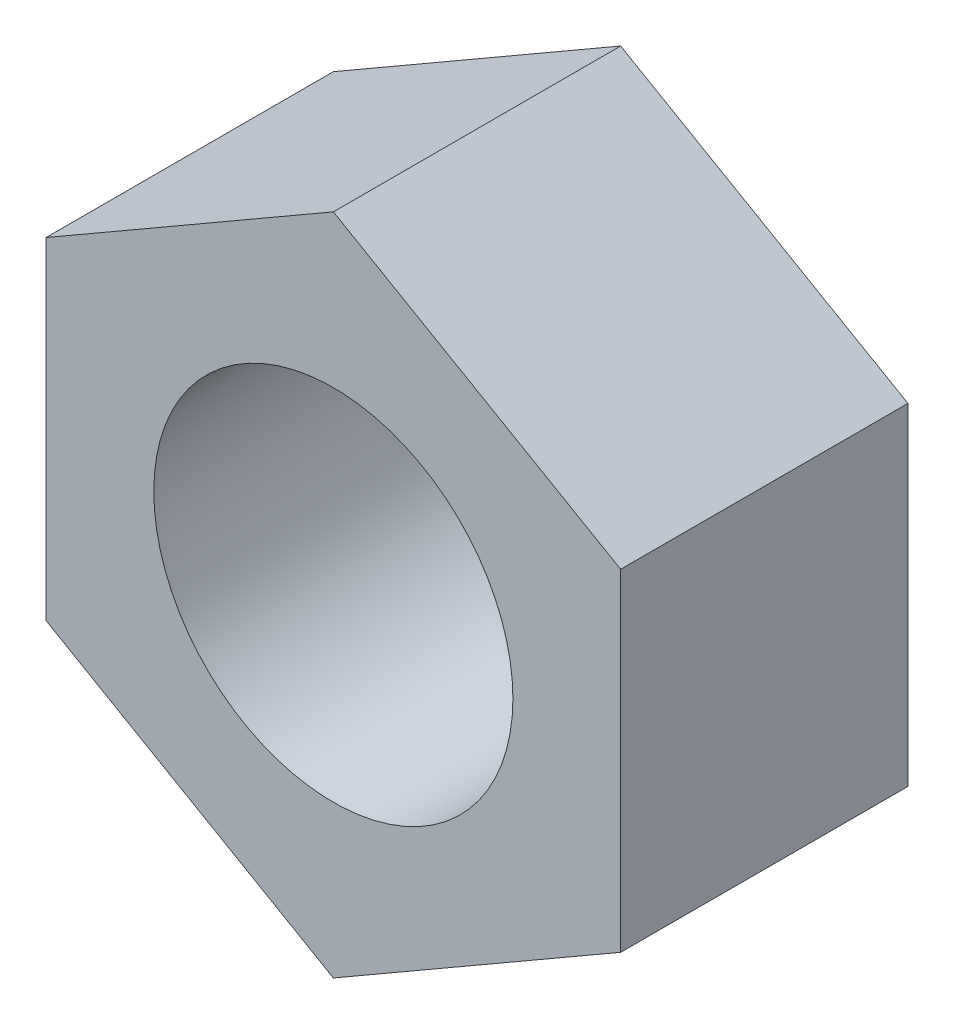
SolidWorks part; units mm, degrees
ref_plane "Přední rovina" through (0, 0, 0) normal (0, 0, 1) x (1, 0, 0)
ref_plane "Horní rovina" through (0, 0, 0) normal (0, 1, 0) x (1, 0, 0)
ref_plane "Pravá rovina" through (0, 0, 0) normal (1, 0, 0) x (0, 0, -1)
sketch "Skica1" plane through (0, 0, 0) normal (0, 0, 1) x (1, 0, 0)
  line L1 (0, -2.7713) -> (2.4, -1.3856)
  line L2 (2.4, -1.3856) -> (2.4, 1.3856)
  line L3 (2.4, 1.3856) -> (0, 2.7713)
  line L4 (0, 2.7713) -> (-2.4, 1.3856)
  line L5 (-2.4, 1.3856) -> (-2.4, -1.3856)
  line L6 (-2.4, -1.3856) -> (0, -2.7713)
  circle A0 centre (0, 0) radius 1.5
  circle A1 centre (0, 0) radius 2.4 construction
  dimension "D1" = 3
  dimension "D2" = 4.8
extrude "Přidat vysunutím1" add sketch "Skica1" along normal blind 2.4
